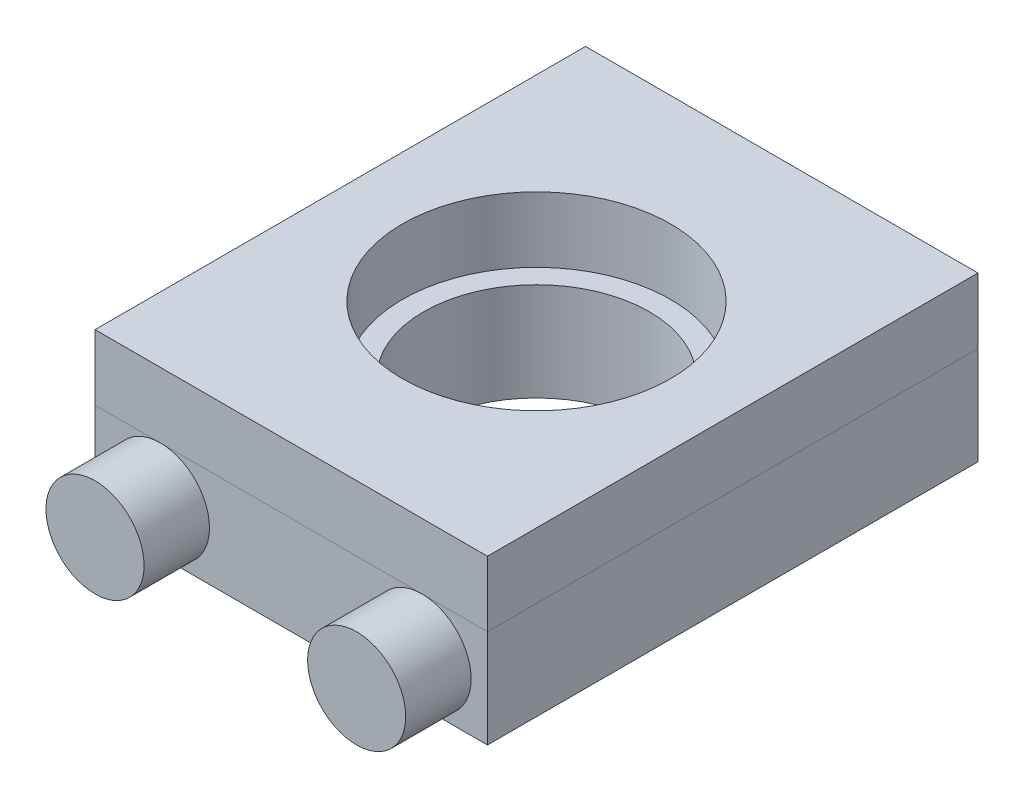
SolidWorks part; units mm, degrees
ref_plane "前视基准面" through (0, 0, 0) normal (0, 0, 1) x (1, 0, 0)
ref_plane "上视基准面" through (0, 0, 0) normal (0, 1, 0) x (1, 0, 0)
ref_plane "右视基准面" through (0, 0, 0) normal (1, 0, 0) x (0, 0, -1)
other "Configuration Table"
sketch "草图1" plane through (0, 0, 0) normal (0, 1, 0) x (1, 0, 0)
  line L0 (6, 15) -> (6, 0) construction
  line L1 (0, 0) -> (12, 0)
  line L2 (0, 0) -> (0, 15)
  line L3 (0, 15) -> (12, 15)
  line L4 (12, 0) -> (12, 15)
  circle A0 centre (6, 7.5) radius 3.45
  circle A1 centre (6, 7.5) radius 4.1
  dimension "D3" = 6.9
  dimension "D4" = 8.2
  dimension "D1" = 12
  dimension "D2" = 15
  dimension "D5" = 7.5
extrude "凸台-拉伸1" add sketch "草图1" along normal blind 3 contours L2 L1 L4 L3 | A0
sketch "草图3" plane through (0, 3, 0) normal (0, 1, 0) x (1, 0, 0)
  line L1 (0, 15) -> (12, 15)
  line L2 (0, 15) -> (0, 0)
  line L3 (0, 0) -> (12, 0)
  line L4 (12, 15) -> (12, 0)
  circle A0 centre (6, 7.5) radius 4.1
  circle A1 centre (6, 7.5) radius 3.45 construction
  circle A2 centre (6, 7.5) radius 3.45
  line M6 (12, 15) -> (0, 15)
  line M7 (0, 15) -> (0, 0)
  line M8 (0, 0) -> (12, 0)
  line M9 (12, 0) -> (12, 15)
  dimension "D1" = 8.2
extrude "凸台-拉伸2" add sketch "草图3" along normal blind 2 contours A0 M9 M6 M7 M8
sketch "草图7" plane through (0, 0, 0) normal (0, 0, 1) x (1, 0, 0)
  line L0 (12, 1.5) -> (0, 1.5) construction
  line L1 (12, 3) -> (12, 0) construction
  line L2 (0, 3) -> (0, 0) construction
  line L3 (6, 5) -> (6, 0) construction
  line L4 (0, 5) -> (12, 5) construction
  line L5 (0, 0) -> (12, 0) construction
  line L6 (0, 5) -> (0, 3) construction
  circle A0 centre (2, 1.5) radius 1.5
  circle A2 centre (10, 1.5) radius 1.5
  dimension "D1" = 3
  dimension "D2" = 4
  dimension "D3" = 2
extrude "凸台-拉伸3" add sketch "草图7" along normal blind 2
